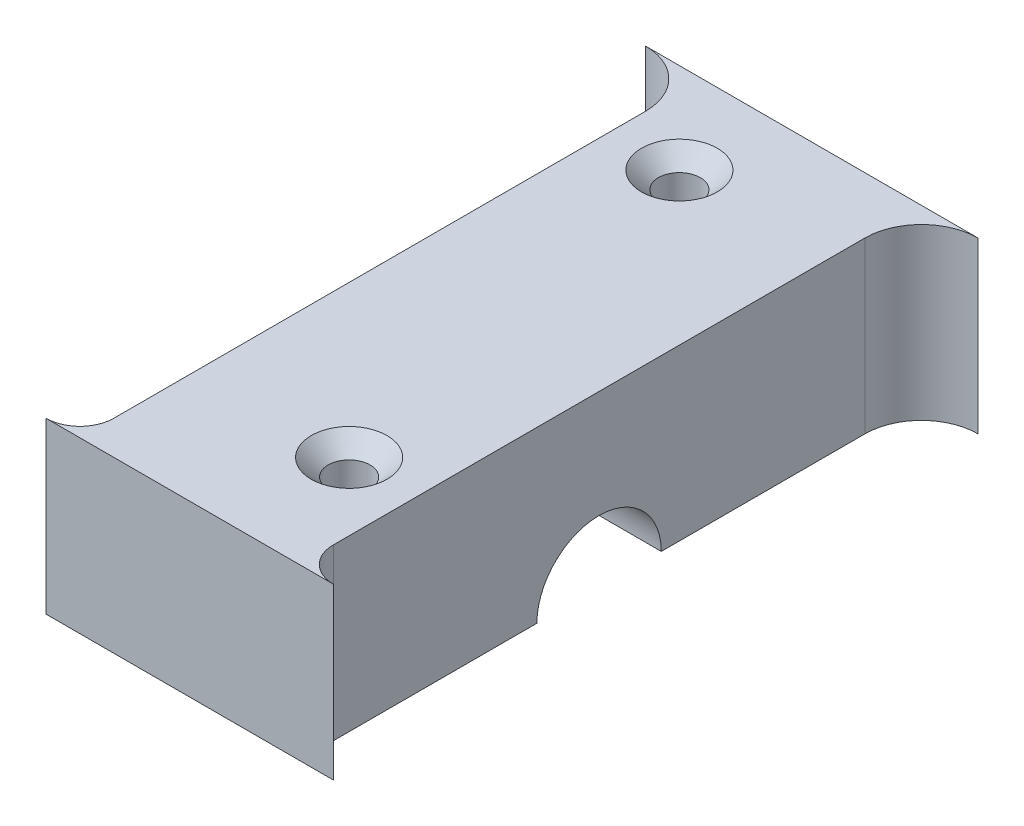
SolidWorks part; units mm, degrees
ref_plane "Plano frontal" through (0, 0, 0) normal (0, 0, 1) x (1, 0, 0)
ref_plane "Plano superior" through (0, 0, 0) normal (0, 1, 0) x (1, 0, 0)
ref_plane "Plano direito" through (0, 0, 0) normal (1, 0, 0) x (0, 0, -1)
sketch "Esboço1" plane through (0, 0, 0) normal (0, 1, 0) x (1, 0, 0)
  line L0 (3, 50) -> (3, 3)
  line L1 (0, 0) -> (25.4, 0)
  line L5 (12.7, 55) -> (12.7, 0) construction
  line L7 (27.4, 55) -> (-2, 55)
  line L8 (22.4, 50) -> (22.4, 3)
  arc A4 (0, 0) -> (3, 3) centre (0, 3) ccw
  arc A7 (-2, 55) -> (3, 50) centre (-2, 50) cw
  arc A8 (27.4, 55) -> (22.4, 50) centre (27.4, 50) ccw
  arc A9 (25.4, 0) -> (22.4, 3) centre (25.4, 3) cw
  dimension "D2" = 5
  dimension "D3" = 3
  dimension "D1" = 47
  dimension "D4" = 3
  dimension "D5" = 3
  dimension "D6" = 5
  dimension "D7" = 5
  dimension "D8" = 29.4
extrude "Ressalto-extrusão1" add sketch "Esboço1" along normal blind 15
ref_plane "Plano1" through (12.7, 0, 0) normal (1, 0, 0) x (0, 0, -1)
sketch "Esboço3" plane through (12.7, 0, 0) normal (1, 0, 0) x (0, 0, -1)
  line L0 (3, 0) -> (50, 0) construction
  circle A0 centre (26.5, 0) radius 5.5
  dimension "D1" = 11
extrude "Corte-extrusão1" cut sketch "Esboço3" against normal through all and the other way through all
sketch "Esboço4" plane through (12.7, 0, 0) normal (1, 0, 0) x (0, 0, -1)
  circle A0 centre (26.5, 0) radius 11.5
  dimension "D1" = 23
extrude "Corte-extrusão2" cut sketch "Esboço4" against normal blind 2 and the other way blind 2
sketch "Esboço6" plane through (0, 0, 0) normal (0, -1, 0) x (1, 0, 0)
  line L0 (0, 0) -> (25.4, 0) construction
  line L1 (22.4, -3) -> (22.4, -21) construction
  line L2 (27.4, -55) -> (-2, -55) construction
  line L3 (3, -50) -> (3, -32) construction
  circle A0 centre (16.4, -10.4) radius 1.85
  circle A1 centre (9, -47) radius 1.85
  dimension "D1" = 3.7
  dimension "D2" = 10.4
  dimension "D3" = 6
  dimension "D4" = 8
  dimension "D5" = 6
extrude "Corte-extrusão4" cut sketch "Esboço6" against normal through all
chamfer "Chanfro1" distance 1.5 angle 45 2 edges at (9, 15, -48.85) (16.4, 15, -12.25)
